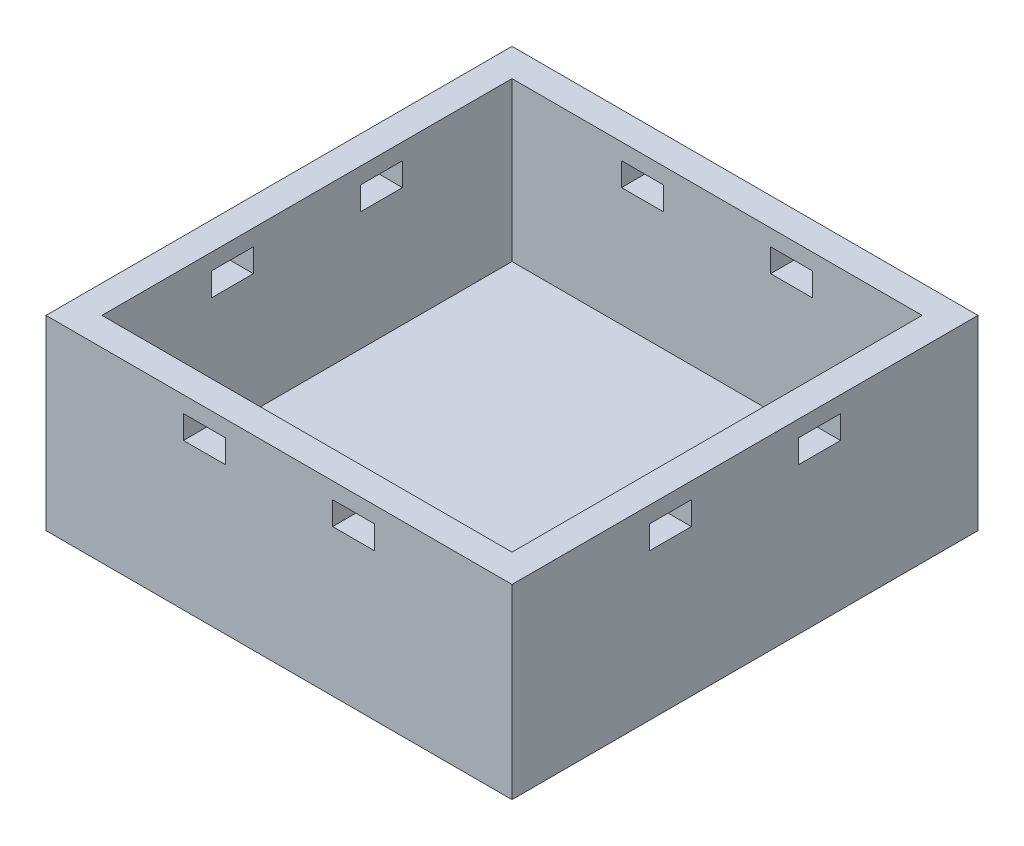
SolidWorks part; units mm, degrees
ref_plane "前视基准面" through (0, 0, 0) normal (0, 0, 1) x (1, 0, 0)
ref_plane "上视基准面" through (0, 0, 0) normal (0, 1, 0) x (1, 0, 0)
ref_plane "右视基准面" through (0, 0, 0) normal (1, 0, 0) x (0, 0, -1)
sketch "草图1" plane through (0, 0, 0) normal (0, 1, 0) x (1, 0, 0)
  line L1 (-25, 25) -> (25, 25)
  line L2 (-25, 25) -> (-25, -25)
  line L3 (-25, -25) -> (25, -25)
  line L4 (25, 25) -> (25, -25)
  line L5 (-25, 25) -> (25, -25) construction
  line L6 (-25, -25) -> (25, 25) construction
  point P0 (0, 0)
  dimension "D1" = 50
  dimension "D2" = 50
extrude "凸台-拉伸1" add sketch "草图1" along normal blind 3
sketch "草图2" plane through (0, 3, 0) normal (0, 1, 0) x (1, 0, 0)
  line L1 (-25, 25) -> (25, 25)
  line L2 (-25, 25) -> (-25, -25)
  line L3 (-25, -25) -> (25, -25)
  line L4 (25, 25) -> (25, -25)
  line L5 (-25, 25) -> (25, -25) construction
  line L6 (-25, -25) -> (25, 25) construction
  line L7 (-22, 22) -> (22, 22)
  line L8 (-22, 22) -> (-22, -22)
  line L9 (-22, -22) -> (22, -22)
  line L10 (22, 22) -> (22, -22)
  line L11 (-22, 22) -> (22, -22) construction
  line L12 (-22, -22) -> (22, 22) construction
  point P0 (0, 0)
  point P7 (0, 0)
  dimension "D1" = 44
extrude "凸台-拉伸2" add sketch "草图2" along normal blind 17
sketch "草图3" plane through (0, 0, 25) normal (0, 0, 1) x (1, 0, 0)
  line L0 (0, 25.074) -> (0, -2.6993) construction
  line L1 (-25, 20) -> (25, 20) construction
  line L2 (-10.25, 18.25) -> (-5.75, 18.25)
  line L3 (-10.25, 18.25) -> (-10.25, 15.75)
  line L4 (-10.25, 15.75) -> (-5.75, 15.75)
  line L5 (-5.75, 18.25) -> (-5.75, 15.75)
  line L6 (-10.25, 18.25) -> (-5.75, 15.75) construction
  line L7 (-10.25, 15.75) -> (-5.75, 18.25) construction
  line L9 (10.25, 15.75) -> (5.75, 18.25) construction
  line L10 (10.25, 18.25) -> (5.75, 15.75) construction
  line L11 (5.75, 18.25) -> (5.75, 15.75)
  line L12 (10.25, 15.75) -> (5.75, 15.75)
  line L13 (10.25, 18.25) -> (10.25, 15.75)
  line L14 (10.25, 18.25) -> (5.75, 18.25)
  line L15 (-25, 20) -> (-25, 0) construction
  point P3 (-8, 17)
  point P8 (0, 25.074)
  point P11 (-9.2406, 16.725)
  point P18 (8, 17)
  dimension "D1" = 1.75
  dimension "D2" = 4.5
  dimension "D3" = 2.5
  dimension "D4" = 14.75
extrude "切除-拉伸1" cut sketch "草图3" against normal through all
sketch "草图4" plane through (25, 0, 0) normal (1, 0, 0) x (0, 0, -1)
  line L0 (0, 25.9684) -> (0, -16.8264) construction
  line L1 (-25, 20) -> (25, 20) construction
  line L2 (-10.25, 18.25) -> (-5.75, 18.25)
  line L3 (-10.25, 18.25) -> (-10.25, 15.75)
  line L4 (-10.25, 15.75) -> (-5.75, 15.75)
  line L5 (-5.75, 18.25) -> (-5.75, 15.75)
  line L6 (-10.25, 18.25) -> (-5.75, 15.75) construction
  line L7 (-10.25, 15.75) -> (-5.75, 18.25) construction
  line L8 (-25, 20) -> (-25, 0) construction
  line L9 (10.25, 15.75) -> (5.75, 18.25) construction
  line L10 (10.25, 18.25) -> (5.75, 15.75) construction
  line L11 (5.75, 18.25) -> (5.75, 15.75)
  line L12 (10.25, 15.75) -> (5.75, 15.75)
  line L13 (10.25, 18.25) -> (10.25, 15.75)
  line L14 (10.25, 18.25) -> (5.75, 18.25)
  point P3 (-8, 17)
  point P16 (8, 17)
  dimension "D1" = 1.75
  dimension "D2" = 2.5
  dimension "D3" = 14.75
  dimension "D4" = 4.5
extrude "切除-拉伸2" cut sketch "草图4" against normal through all
